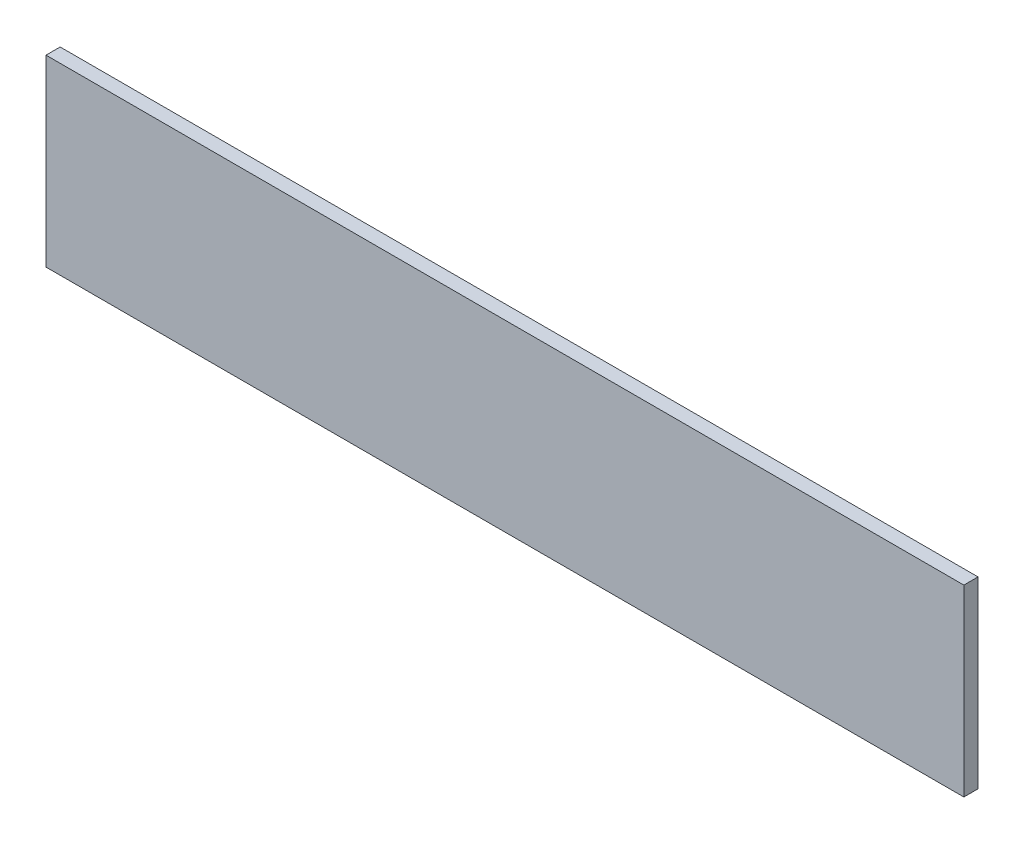
SolidWorks part; units mm, degrees
ref_plane "Alzado" through (0, 0, 0) normal (0, 0, 1) x (1, 0, 0)
ref_plane "Planta" through (0, 0, 0) normal (0, 1, 0) x (1, 0, 0)
ref_plane "Vista lateral" through (0, 0, 0) normal (1, 0, 0) x (0, 0, -1)
sketch "Croquis1" plane through (0, 0, 0) normal (0, 0, 1) x (1, 0, 0)
  line L1 (-154.4788, 17.025) -> (40.0931, 17.025)
  line L2 (-154.4788, 17.025) -> (-154.4788, -21.8893)
  line L3 (-154.4788, -21.8893) -> (40.0931, -21.8893)
  line L4 (40.0931, 17.025) -> (40.0931, -21.8893)
  line L5 (-154.4788, 17.025) -> (40.0931, -21.8893) construction
  line L6 (-154.4788, -21.8893) -> (40.0931, 17.025) construction
  point P0 (-57.1928, -2.4321)
extrude "Saliente-Extruir1" add sketch "Croquis1" along normal blind 3
